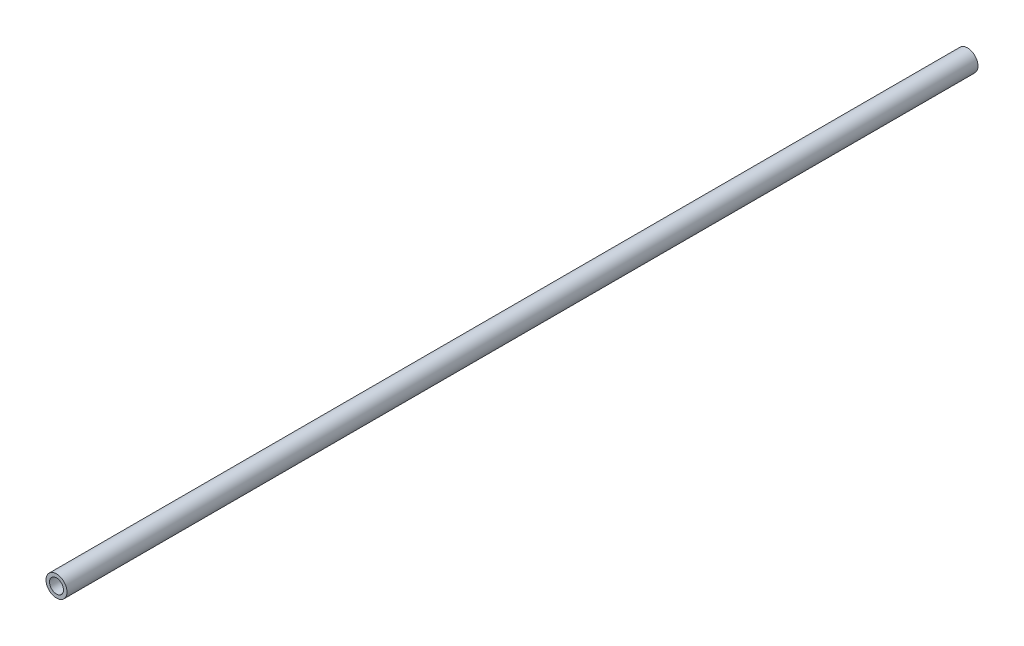
SolidWorks part; units mm, degrees
ref_plane "前视基准面" through (0, 0, 0) normal (0, 0, 1) x (1, 0, 0)
ref_plane "上视基准面" through (0, 0, 0) normal (0, 1, 0) x (1, 0, 0)
ref_plane "右视基准面" through (0, 0, 0) normal (1, 0, 0) x (0, 0, -1)
other "Configuration Table"
sketch "草图1" plane through (0, 0, 0) normal (0, 0, 1) x (1, 0, 0)
  circle A0 centre (0, 0) radius 2
  circle A1 centre (0, 0) radius 3
  dimension "D1" = 4
  dimension "D2" = 6
extrude "凸台-拉伸1" add sketch "草图1" along normal blind 260
